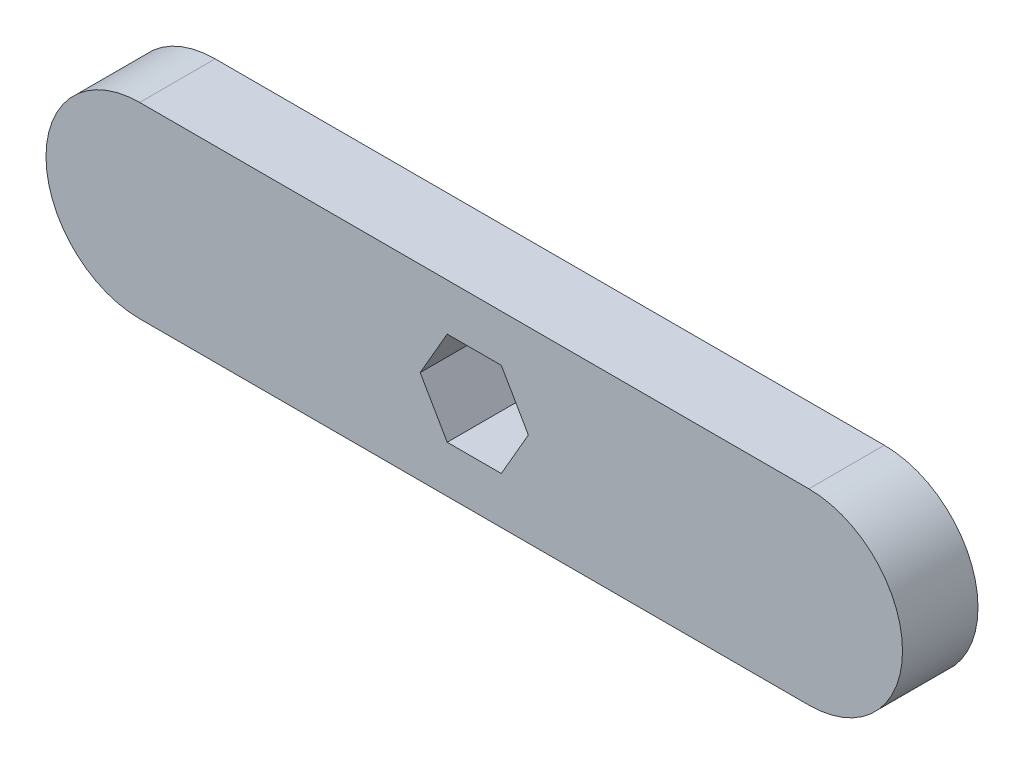
SolidWorks part; units mm, degrees
material "Acrylic (Medium-high impact)"
ref_plane "Front Plane" through (0, 0, 0) normal (0, 0, 1) x (1, 0, 0)
ref_plane "Top Plane" through (0, 0, 0) normal (0, 1, 0) x (1, 0, 0)
ref_plane "Right Plane" through (0, 0, 0) normal (1, 0, 0) x (0, 0, -1)
sketch "Sketch1" plane through (0, 0, 0) normal (0, 0, 1) x (1, 0, 0)
  line L0 (-25, 0) -> (25, 0) construction
  line L1 (0, -654.3154) -> (0, 49345.6846) construction
  line L2 (-25, 7) -> (25, 7)
  line L3 (-2.0207, 3.5) -> (-4.0415, 0)
  line L4 (-4.0415, 0) -> (-2.0207, -3.5)
  line L5 (-2.0207, -3.5) -> (2.0207, -3.5)
  line L6 (2.0207, -3.5) -> (4.0415, 0)
  line L7 (-245.8122, 0) -> (49754.1878, 0) construction
  line L8 (4.0415, 0) -> (2.0207, 3.5)
  line L9 (2.0207, 3.5) -> (-2.0207, 3.5)
  line L10 (-25, -7) -> (25, -7)
  circle A0 centre (0, 0) radius 3.5 construction
  arc A1 (-25, 7) -> (-25, -7) centre (-25, 0) ccw
  arc A2 (25, -7) -> (25, 7) centre (25, 0) ccw
  point P7 (0, 0)
  dimension "D1" = 7
  dimension "D2" = 14
  dimension "D3" = 25
extrude "Boss-Extrude2" add sketch "Sketch1" along normal blind 5.64
